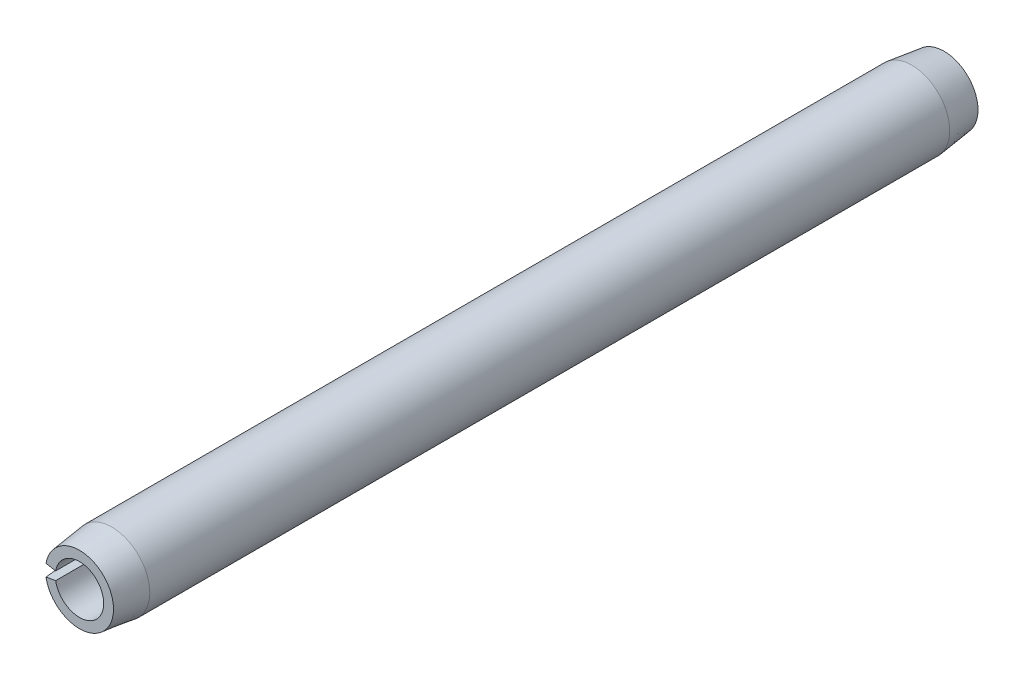
SolidWorks part; units mm, degrees
material "AISI 316 Stainless Steel Sheet (SS)"
ref_plane "Front Plane" through (0, 0, 0) normal (0, 0, 1) x (1, 0, 0)
ref_plane "Top Plane" through (0, 0, 0) normal (0, 1, 0) x (1, 0, 0)
ref_plane "Right Plane" through (0, 0, 0) normal (1, 0, 0) x (0, 0, -1)
sketch "Sketch1" plane through (0, 0, 0) normal (0, 0, 1) x (1, 0, 0)
  line L0 (0.5334, 0) -> (0.8382, 0) construction
  line L1 (-0.8255, 0.1456) -> (-0.5253, 0.0926)
  line L2 (-0.5253, -0.0926) -> (-0.8255, -0.1456)
  arc A0 (-0.8255, -0.1456) -> (-0.8255, 0.1456) centre (0, 0) ccw
  arc A1 (-0.5253, -0.0926) -> (-0.5253, 0.0926) centre (0, 0) ccw
  dimension "OD" = 1.6764
  dimension "Wall thickness" = 0.3048
  dimension "D3" = 20
extrude "Extrude1" add sketch "Sketch1" along normal mid plane 19.05
sketch "Sketch2" plane through (0, 0, 0) normal (1, 0, 0) x (0, 0, -1)
  line L0 (0, -0.8382) -> (0, 0.8382) construction
  line L1 (9.525, 0) -> (-9.525, 0) construction
  line L2 (9.525, -0.5334) -> (9.525, 0.5334) construction
  line L3 (9.525, 0.8382) -> (-9.525, 0.8382) construction
  line L4 (9.525, 0.8382) -> (9.525, 0.7493)
  line L5 (9.525, 0.7493) -> (8.8138, 0.8382)
  line L6 (8.8138, 0.8382) -> (9.525, 0.8382)
  line L7 (9.525, -0.8382) -> (9.525, 0.8382) construction
  line L8 (-8.8138, 0.8382) -> (-9.525, 0.8382)
  line L9 (-9.525, 0.7493) -> (-8.8138, 0.8382)
  line L10 (-9.525, 0.8382) -> (-9.525, 0.7493)
  line L11 (8.8138, -0.8382) -> (9.525, -0.8382) construction
  line L12 (9.525, -0.7493) -> (8.8138, -0.8382) construction
  line L13 (9.525, -0.8382) -> (9.525, -0.7493) construction
  dimension "B" = 1.4986
  dimension "Chamfer max" = 0.7112
revolve "Cut-Revolve1" cut sketch "Sketch2" angle 360 about L1
sketch "Sketch3" plane through (0, 0, 0) normal (0, 0, 1) x (1, 0, 0)
  line L0 (0.5334, 0) -> (0.8382, 0) construction
  line L1 (0.5334, 0) -> (0.8382, 0)
  circle A0 centre (0, 0) radius 0.8382
  circle A1 centre (0, 0) radius 0.5334
  arc A2 (-0.8255, -0.1456) -> (-0.8255, 0.1456) centre (0, 0) ccw construction
  arc A3 (-0.5253, -0.0926) -> (-0.5253, 0.0926) centre (0, 0) ccw construction
